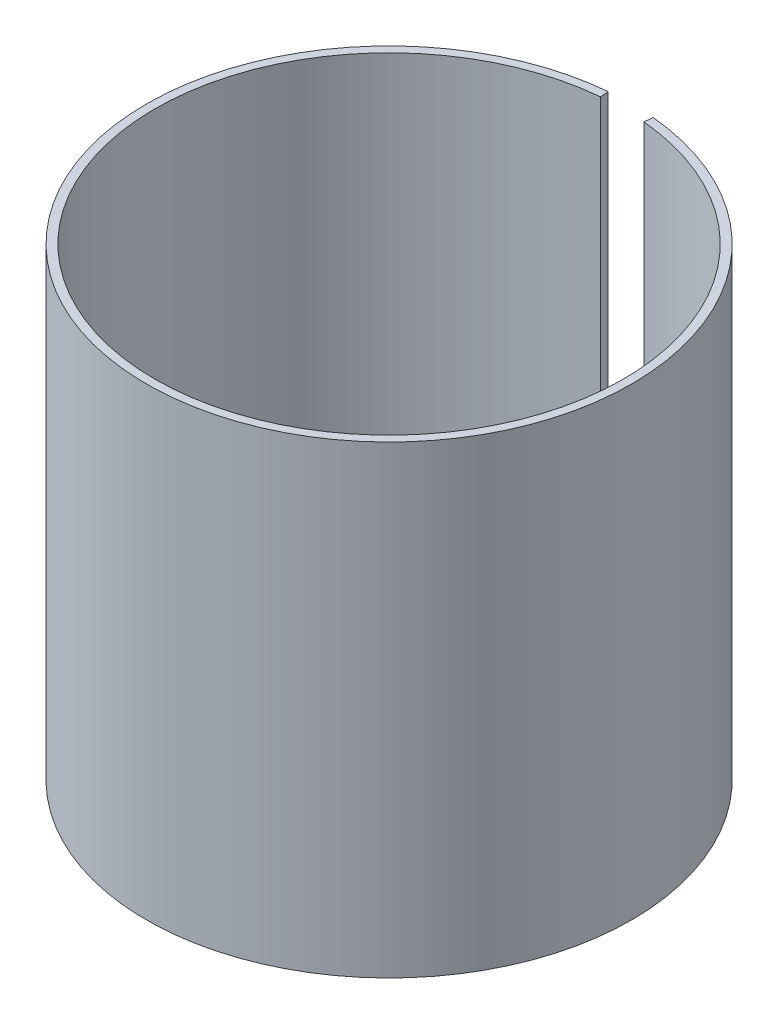
SolidWorks part; units mm, degrees
material "AISI 304"
ref_plane "Спереди" through (0, 0, 0) normal (0, 0, 1) x (1, 0, 0)
ref_plane "Сверху" through (0, 0, 0) normal (0, 1, 0) x (1, 0, 0)
ref_plane "Справа" through (0, 0, 0) normal (1, 0, 0) x (0, 0, -1)
other "Configuration Table"
sketch "Эскиз1" plane through (0, 0, 0) normal (0, 1, 0) x (1, 0, 0)
  circle A0 centre (0, 0) radius 86.5
  circle A1 centre (0, 0) radius 83.5
  dimension "D1" = 173
  dimension "D2" = 3
extrude "Бобышка-Вытянуть1" add sketch "Эскиз1" along normal blind 165.5
sketch "Эскиз2" plane through (0, 165.5, 0) normal (0, 1, 0) x (1, 0, 0)
  line L0 (0, 0) -> (0, 114.8498) construction
  line L1 (-8, 86.1293) -> (-7.7225, 83.1421)
  line L2 (7.7225, 83.1421) -> (8, 86.1293)
  line L3 (7.7225, 83.1421) -> (0, 0) construction
  arc A0 (-7.7225, 83.1421) -> (7.7225, 83.1421) centre (0, 0) cw
  circle A1 centre (0, 0) radius 83.5 construction
  arc A2 (-8, 86.1293) -> (8, 86.1293) centre (0, 0) cw
  circle A3 centre (0, 0) radius 86.5 construction
  dimension "D1" = 16
extrude "Вырез-Вытянуть1" cut sketch "Эскиз2" against normal through all both and the other way through all
